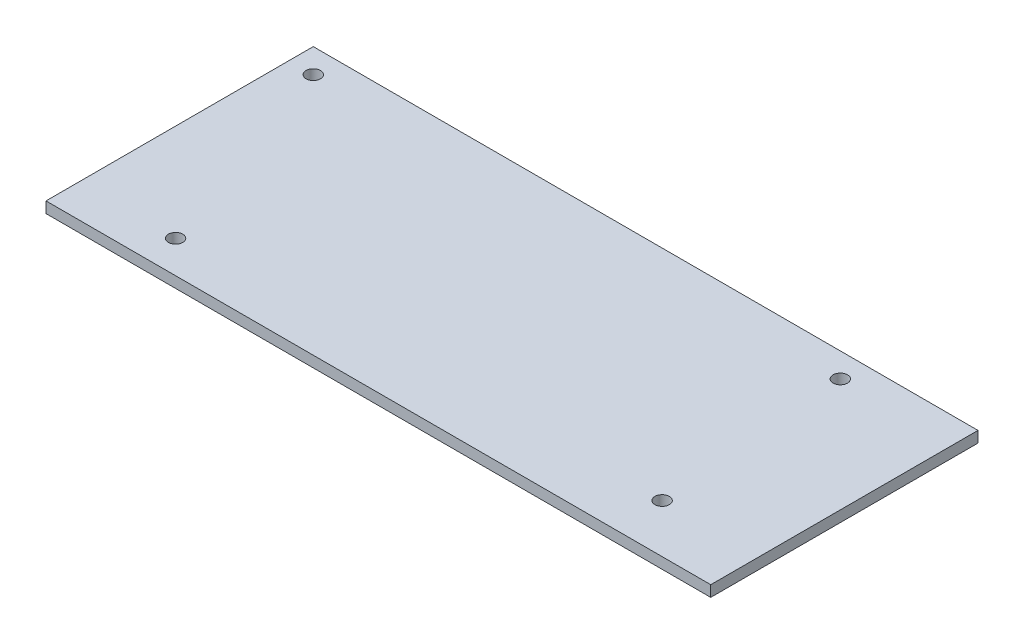
SolidWorks part; units mm, degrees
ref_plane "Front Plane" through (0, 0, 0) normal (0, 0, 1) x (1, 0, 0)
ref_plane "Top Plane" through (0, 0, 0) normal (0, 1, 0) x (1, 0, 0)
ref_plane "Right Plane" through (0, 0, 0) normal (1, 0, 0) x (0, 0, -1)
sketch "Sketch1" plane through (0, 0, 0) normal (0, 1, 0) x (1, 0, 0)
  line L1 (-52.1208, 20.955) -> (52.1208, 20.955)
  line L2 (-52.1208, 20.955) -> (-52.1208, -20.955)
  line L3 (-52.1208, -20.955) -> (52.1208, -20.955)
  line L4 (52.1208, 20.955) -> (52.1208, -20.955)
  line L5 (-52.1208, 20.955) -> (52.1208, -20.955) construction
  line L6 (-52.1208, -20.955) -> (52.1208, 20.955) construction
  point P0 (0, 0)
  dimension "D1" = 104.2416
  dimension "D2" = 41.91
extrude "Boss-Extrude1" add sketch "Sketch1" along normal mid plane 1.7272
sketch "Sketch3" plane through (0, 0.8636, 0) normal (0, 1, 0) x (1, 0, 0)
  line L0 (-52.1208, 20.955) -> (-52.1208, -20.955) construction
  line L1 (52.1208, 20.955) -> (-52.1208, 20.955) construction
  line L2 (-52.1208, -20.955) -> (52.1208, -20.955) construction
  line L3 (52.1208, -20.955) -> (52.1208, 20.955) construction
  point P0 (-48.3108, 17.145)
  point P1 (-36.8808, -15.875)
  point P2 (34.3408, 17.145)
  point P3 (36.8808, -13.335)
  dimension "D1" = 3.81
  dimension "D2" = 3.81
  dimension "D3" = 15.24
  dimension "D4" = 5.08
  dimension "D5" = 3.81
  dimension "D6" = 17.78
  dimension "D7" = 7.62
  dimension "D8" = 15.24
hole_wizard "#4-40 Tapped Hole1" positions "Sketch4" profile "Sketch5" tap size "#4-40" standard "ANSI Inch" end condition through all
sketch "Sketch4" plane through (0, 0.8636, 0) normal (0, 1, 0) x (1, 0, 0)
  point P0 (-48.3108, 17.145)
  point P3 (-36.8808, -15.875)
  point P6 (34.3408, 17.145)
  point P9 (36.8808, -13.335)
sketch "Sketch5" plane through (-48.3108, 0.8636, -17.145) normal (1, 0, 0) x (0, 0, 1)
  line L0 (0, 0) -> (0, 1.7272)
  line L1 (0, 1.7272) -> (1.1303, 1.7272)
  line L2 (1.1303, 1.7272) -> (1.1303, 0)
  line L5 (1.1303, 0) -> (0, 0)
  line L11 (0, -6.35) -> (0, 107.95) construction
  dimension "Thread Major Dia." = 2.2606
  dimension "Thru Tap Drill Depth" = 1.7272
